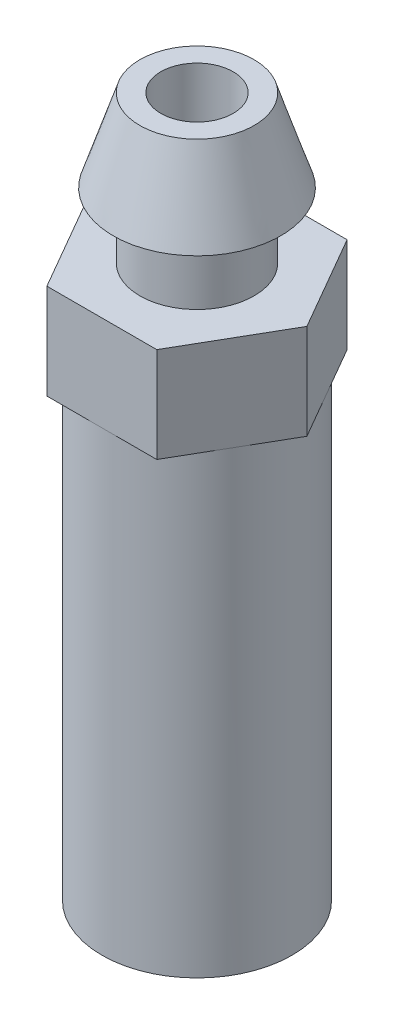
SolidWorks part; units mm, degrees
ref_plane "Front Plane" through (0, 0, 0) normal (0, 0, 1) x (1, 0, 0)
ref_plane "Top Plane" through (0, 0, 0) normal (0, 1, 0) x (1, 0, 0)
ref_plane "Right Plane" through (0, 0, 0) normal (1, 0, 0) x (0, 0, -1)
sketch "Sketch1" plane through (0, 0, 0) normal (0, 1, 0) x (1, 0, 0)
  circle A0 centre (0, 0) radius 3.175
  dimension "D1" = 6.35
extrude "Boss-Extrude1" add sketch "Sketch1" along normal blind 15.24
sketch "Sketch2" plane through (0, 15.24, 0) normal (0, 1, 0) x (1, 0, 0)
  line L1 (3.6662, 0) -> (1.8331, 3.175)
  line L2 (1.8331, 3.175) -> (-1.8331, 3.175)
  line L3 (-1.8331, 3.175) -> (-3.6662, 0)
  line L4 (-3.6662, 0) -> (-1.8331, -3.175)
  line L5 (-1.8331, -3.175) -> (1.8331, -3.175)
  line L6 (1.8331, -3.175) -> (3.6662, 0)
  circle A0 centre (0, 0) radius 3.175 construction
  dimension "D1" = 6.35
extrude "Boss-Extrude2" add sketch "Sketch2" along normal blind 3.175
sketch "Sketch3" plane through (0, 18.415, 0) normal (0, 1, 0) x (1, 0, 0)
  circle A0 centre (0, 0) radius 1.905
  dimension "D1" = 3.81
extrude "Boss-Extrude3" add sketch "Sketch3" along normal blind 2.032
sketch "Sketch7" plane through (0, 0, 0) normal (0, 0, 1) x (1, 0, 0)
  line L0 (0, 20.5947) -> (2.794, 20.5947)
  line L1 (2.794, 20.5947) -> (1.905, 23.3379)
  line L2 (1.905, 23.3379) -> (0, 23.3379)
  line L3 (0, 23.3379) -> (0, 20.5947)
  dimension "D1" = 2.7432
  dimension "D2" = 2.794
  dimension "D3" = 1.905
revolve "Revolve1" add sketch "Sketch7" angle 360 about L3
sketch "Sketch8" plane through (0, 23.3379, 0) normal (0, 1, 0) x (1, 0, 0)
  circle A0 centre (0, 0) radius 1.2065
  dimension "D1" = 2.413
extrude "Cut-Extrude1" cut sketch "Sketch8" against normal blind 9.652
